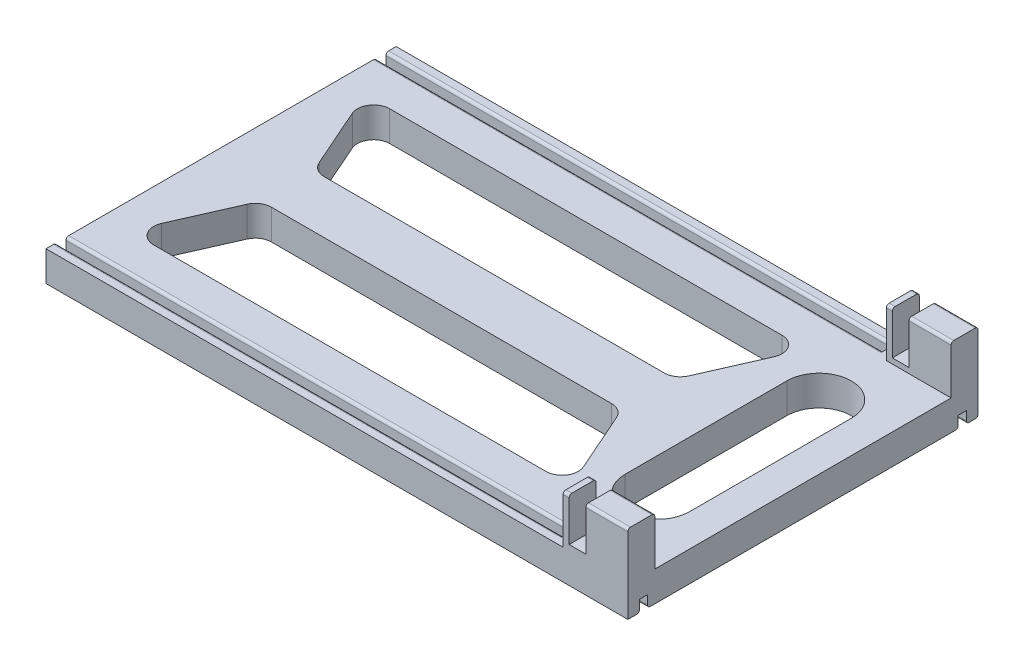
SolidWorks part; units mm, degrees
material "PETG"
ref_plane "Front Plane" through (0, 0, 0) normal (0, 0, 1) x (1, 0, 0)
ref_plane "Top Plane" through (0, 0, 0) normal (0, 1, 0) x (1, 0, 0)
ref_plane "Right Plane" through (0, 0, 0) normal (1, 0, 0) x (0, 0, -1)
sketch "Sketch1" plane through (0, 0, 0) normal (1, 0, 0) x (0, 0, -1)
  line L0 (0, -0.9868) -> (0, -24.6737) construction
  line L1 (-28.79, -0.9868) -> (28.79, -0.9868)
  line L2 (-32.5, -0.9868) -> (-30.6, -0.9868)
  line L3 (-30.6, -0.9868) -> (-30.6, -3.1368)
  line L4 (-30.6, -3.1368) -> (-28.79, -3.1368)
  line L5 (-28.79, -3.1368) -> (-28.79, -0.9868)
  line L7 (-32.5, -0.9868) -> (-32.5, -6.5868)
  line L13 (0, -19.1998) -> (0, -0.9868) construction
  line L14 (66.29, -4.4368) -> (66.29, -6.5868)
  line L19 (-28.8314, -4.4368) -> (-28.8314, -6.5868)
  line L20 (-30.3407, -4.4368) -> (-28.8314, -4.4368)
  line L21 (-30.3407, -6.5868) -> (-30.3407, -4.4368)
  line L22 (-32.5, -6.5868) -> (-30.3407, -6.5868)
  line L23 (-28.8314, -6.5868) -> (28.8314, -6.5868)
  line L24 (32.5, -6.5868) -> (30.3407, -6.5868)
  line L25 (30.3407, -6.5868) -> (30.3407, -4.4368)
  line L26 (30.3407, -4.4368) -> (28.8314, -4.4368)
  line L27 (28.8314, -4.4368) -> (28.8314, -6.5868)
  line L28 (32.5, -0.9868) -> (32.5, -6.5868)
  line L29 (28.79, -3.1368) -> (28.79, -0.9868)
  line L30 (30.6, -3.1368) -> (28.79, -3.1368)
  line L31 (30.6, -0.9868) -> (30.6, -3.1368)
  line L32 (32.5, -0.9868) -> (30.6, -0.9868)
  point P4 (0, -6.5868)
  point P18 (0, -0.9868)
  point P24 (-2.21, -6.5868)
  point P25 (32.5, -3.7868)
  point P26 (-32.5, -3.7868)
  point P30 (2.21, -6.5868)
  dimension "D1" = 65
  dimension "D2" = 2.8
  dimension "D3" = 1.9
  dimension "D4" = 2.15
  dimension "D6" = 1.81
extrude "Boss-Extrude1" add sketch "Sketch1" along normal blind 108 contours L28 L32 L31 L30 L29 L1 L5 L4 L3 L2 L7 L22 L21 L20 L19 L23 L27 L26 L25 L24
sketch "Sketch3" plane through (0, 0, 0) normal (-1, 0, 0) x (0, 0, 1)
  line L0 (-19.6429, -4.2462) -> (-13.897, -4.2462)
  line L1 (-21.0459, -0.9868) -> (-21.0459, -6.5868)
  line L2 (28.79, -0.9868) -> (-28.79, -0.9868) construction
  line L3 (28.8314, -6.5868) -> (-28.8314, -6.5868) construction
  line L4 (-21.0459, -6.5868) -> (-12.4271, -6.5868)
  line L5 (-12.4271, -6.5868) -> (-12.4271, -0.9868)
  line L6 (-12.4271, -0.9868) -> (-21.0459, -0.9868)
sketch "Sketch4" plane through (0, 0, -32.5) normal (0, 0, -1) x (-1, 0, 0)
  line L0 (0, -0.9868) -> (0, 4.0132)
  line L2 (0, -0.9868) -> (0, -6.5868) construction
  line L3 (0, 4.0132) -> (-10, 4.0132)
  line L4 (-10, 4.0132) -> (-10, -0.9868)
  line L6 (0, -0.9868) -> (-10, -0.9868)
  line L7 (-108, -0.9868) -> (0, -0.9868) construction
  dimension "D1" = 10
  dimension "D2" = 5
sketch "Sketch5" plane through (0, -0.9868, 0) normal (0, 1, 0) x (1, 0, 0)
  line L0 (108, -27.5) -> (94.1955, -27.5)
  line L1 (108, -28.79) -> (108, 28.79) construction
  line L2 (94.1955, -27.5) -> (94.1955, -32.5)
  line L3 (108, -32.5) -> (0, -32.5) construction
  line L4 (94.1955, -32.5) -> (108, -32.5)
  line L5 (108, -32.5) -> (108, -27.5)
  dimension "D1" = 5
extrude "Boss-Extrude3" add sketch "Sketch5" against normal up to next
sketch "Sketch7" plane through (0, -0.9868, 0) normal (0, 1, 0) x (1, 0, 0)
  line L0 (108, -32.5) -> (108, -27.5)
  line L1 (108, -32.5) -> (108, 28.79) construction
  line L2 (108, -27.5) -> (96, -27.5)
  line L3 (96, -27.5) -> (96, -32.5)
  line L4 (108, -32.5) -> (0, -32.5) construction
  line L5 (96, -32.5) -> (108, -32.5)
  dimension "D1" = 5
  dimension "D2" = 12
extrude "Boss-Extrude4" add sketch "Sketch7" along normal blind 9
mirror "Mirror1" about plane through (0, 0, 0) normal (0, 0, 1) of "Boss-Extrude4"
mirror "Mirror2" about plane through (0, 0, 0) normal (0, 0, 1) of "Boss-Extrude3"
sketch "Sketch8" plane through (0, 8.0132, 0) normal (0, 1, 0) x (1, 0, 0)
  line L0 (100.2, -32.5) -> (100.2, -27.5)
  line L1 (96, -32.5) -> (108, -32.5) construction
  line L2 (108, -27.5) -> (96, -27.5) construction
  line L3 (100.2, -27.5) -> (97.1, -27.5)
  line L4 (97.1, -27.5) -> (97.1, -32.5)
  line L5 (97.1, -32.5) -> (100.2, -32.5)
  line L6 (108, -32.5) -> (108, -27.5) construction
  dimension "D1" = 7.8
  dimension "D2" = 3.1
extrude "Cut-Extrude1" cut sketch "Sketch8" against normal blind 8
mirror "Mirror3" about plane through (0, 0, 0) normal (0, 0, 1) of "Cut-Extrude1"
fillet "Fillet1" radius 0.5 1 edges at (47.0978, -0.9868, 30.6)
fillet "Fillet2" radius 0.5 1 edges at (47.0978, -0.9868, 28.79)
fillet "Fillet3" radius 0.5 1 edges at (54, -6.5868, 30.3407)
fillet "Fillet4" radius 0.5 1 edges at (54, -6.5868, 28.8314)
fillet "Fillet5" radius 0.5 1 edges at (104.1, 8.0132, 32.5)
fillet "Fillet6" radius 0.5 1 edges at (96.55, 8.0132, 32.5)
fillet "Fillet7" radius 0.5 10 edges at (47.0978, -0.9868, -28.79) (54, -6.5868, -28.8314) (54, -6.5868, -30.3407) (54, -6.5868, -32.5) (96.55, 8.0132, -27.5) (96.55, 8.0132, -32.5) (104.1, 8.0132, -32.5) (104.1, 8.0132, -27.5) (96.55, 8.0132, 27.5) (104.1, 8.0132, 27.5)
fillet "Fillet8" radius 0.5 1 edges at (47.0978, -0.9868, -30.6)
sketch "Sketch9" plane through (0, -0.9868, 0) normal (0, 1, 0) x (1, 0, 0)
  line L0 (96, -15) -> (96, 15) construction
  line L1 (90, -15) -> (90, 15)
  line L2 (102, -15) -> (102, 15)
  line L3 (86.8, 21.9) -> (79.3, 4.9)
  line L4 (79.3, 4.9) -> (12.3, 4.9)
  line L5 (12.3, 4.9) -> (4.8, 21.9)
  line L6 (4.8, 21.9) -> (86.8, 21.9)
  line L7 (0, 0) -> (108, 0)
  line L8 (108, -27.5) -> (108, 27.5) construction
  line L9 (4.8, -21.9) -> (86.8, -21.9)
  line L10 (12.3, -4.9) -> (4.8, -21.9)
  line L11 (79.3, -4.9) -> (12.3, -4.9)
  line L12 (86.8, -21.9) -> (79.3, -4.9)
  arc A0 (90, -15) -> (102, -15) centre (96, -15) ccw
  arc A1 (102, 15) -> (90, 15) centre (96, 15) ccw
  point P2 (96, 0)
  dimension "D3" = 6
  dimension "D1" = 30
  dimension "D2" = 0
  dimension "D4" = 12
  dimension "D5" = 67
  dimension "D6" = 82
  dimension "D7" = 7.5
  dimension "D8" = 6.9
  dimension "D9" = 17
  dimension "D10" = 9.2
extrude "Cut-Extrude2" cut sketch "Sketch9" against normal blind 10
fillet "Fillet9" radius 3 8 edges at (86.8, -3.7868, 21.9) (79.3, -3.7868, 4.9) (4.8, -3.7868, 21.9) (12.3, -3.7868, 4.9) (12.3, -3.7868, -4.9) (4.8, -3.7868, -21.9) (86.8, -3.7868, -21.9) (79.3, -3.7868, -4.9)
